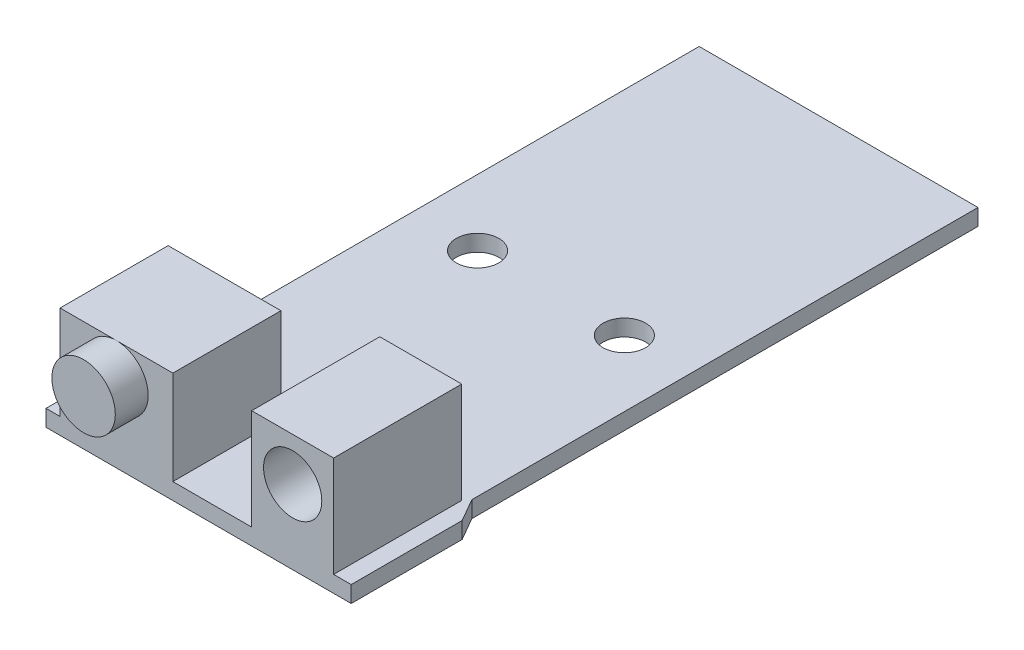
SolidWorks part; units mm, degrees
ref_plane "Front Plane" through (0, 0, 0) normal (0, 0, 1) x (1, 0, 0)
ref_plane "Top Plane" through (0, 0, 0) normal (0, 1, 0) x (1, 0, 0)
ref_plane "Right Plane" through (0, 0, 0) normal (1, 0, 0) x (0, 0, -1)
sketch "Sketch1" plane through (0, 0, 0) normal (0, 1, 0) x (1, 0, 0)
  line L0 (0, 0) -> (0, 69.2) construction
  line L1 (-15.075, 69.2) -> (15.075, 69.2)
  line L2 (15.075, 69.2) -> (15.075, 14.4682)
  line L3 (15.075, 14.4682) -> (16.5, 12)
  line L4 (16.5, 12) -> (16.5, 0)
  line L5 (16.5, 0) -> (-16.5, 0)
  line L6 (-16.5, 12) -> (-16.5, 0)
  line L7 (-15.075, 14.4682) -> (-16.5, 12)
  line L8 (-15.075, 69.2) -> (-15.075, 14.4682)
  point P11 (15.075, 19.5802)
  dimension "D1" = 30.15
  dimension "D2" = 69.2
  dimension "D3" = 12
  dimension "D4" = 33
  dimension "D5" = 30
extrude "Boss-Extrude1" add sketch "Sketch1" along normal blind 1.778
sketch "Sketch2" plane through (0, 1.778, 0) normal (0, 1, 0) x (1, 0, 0)
  line L0 (-16.5, 0) -> (16.5, 0) construction
  line L1 (5.74, 13.85) -> (14.6, 13.85)
  line L2 (5.74, 13.85) -> (5.74, 0)
  line L3 (5.74, 0) -> (14.6, 0)
  line L4 (14.6, 13.85) -> (14.6, 0)
  line L5 (5.74, 13.85) -> (14.6, 0) construction
  line L6 (5.74, 0) -> (14.6, 13.85) construction
  line L7 (16.5, 0) -> (16.5, 12) construction
  point P4 (10.17, 6.925)
  dimension "D1" = 13.85
  dimension "D2" = 8.86
  dimension "D3" = 1.9
extrude "Boss-Extrude2" add sketch "Sketch2" along normal blind 10.9
sketch "Sketch3" plane through (0, 1.778, 0) normal (0, 1, 0) x (1, 0, 0)
  line L0 (-7.9375, 38.1) -> (7.9375, 38.1) construction
  line L1 (0, 38.1) -> (0, 0) construction
  circle A0 centre (-7.9375, 38.1) radius 2.3
  circle A1 centre (7.9375, 38.1) radius 2.3
  dimension "D2" = 4.6
  dimension "D1" = 15.875
  dimension "D3" = 38.1
extrude "Cut-Extrude1" cut sketch "Sketch3" against normal through all
sketch "Sketch4" plane through (0, 1.778, 0) normal (0, 1, 0) x (1, 0, 0)
  line L0 (-16.5, 0) -> (5.74, 0) construction
  line L1 (-14.976, 0) -> (-2.784, 0)
  line L2 (-14.976, 0) -> (-14.976, 11.684)
  line L3 (-14.976, 11.684) -> (-2.784, 11.684)
  line L4 (-2.784, 0) -> (-2.784, 11.684)
  line L5 (-14.976, 0) -> (-2.784, 11.684) construction
  line L6 (-14.976, 11.684) -> (-2.784, 0) construction
  line L7 (-16.5, 12) -> (-16.5, 0) construction
  point P4 (-8.88, 5.842)
  dimension "D1" = 12.192
  dimension "D2" = 11.684
  dimension "D3" = 1.524
extrude "Boss-Extrude3" add sketch "Sketch4" along normal blind 10.16
sketch "Sketch5" plane through (0, 0, 0) normal (0, 0, 1) x (1, 0, 0)
  line L0 (-14.976, 11.938) -> (-2.784, 11.938) construction
  line L1 (-8.88, 8.509) -> (-8.88, 11.938) construction
  circle A0 centre (-8.88, 8.509) radius 3.429
  dimension "D1" = 6.858
extrude "Boss-Extrude4" add sketch "Sketch5" along normal blind 3.556
sketch "Sketch6" plane through (0, 0, 0) normal (0, 0, 1) x (1, 0, 0)
  line L0 (5.74, 12.678) -> (14.6, 12.678) construction
  line L1 (10.17, 12.678) -> (10.17, 8.0044) construction
  circle A0 centre (10.17, 8.0044) radius 3.1496
  dimension "D1" = 6.2992
  dimension "D2" = 1.524
extrude "Cut-Extrude2" cut sketch "Sketch6" against normal blind 11.656
